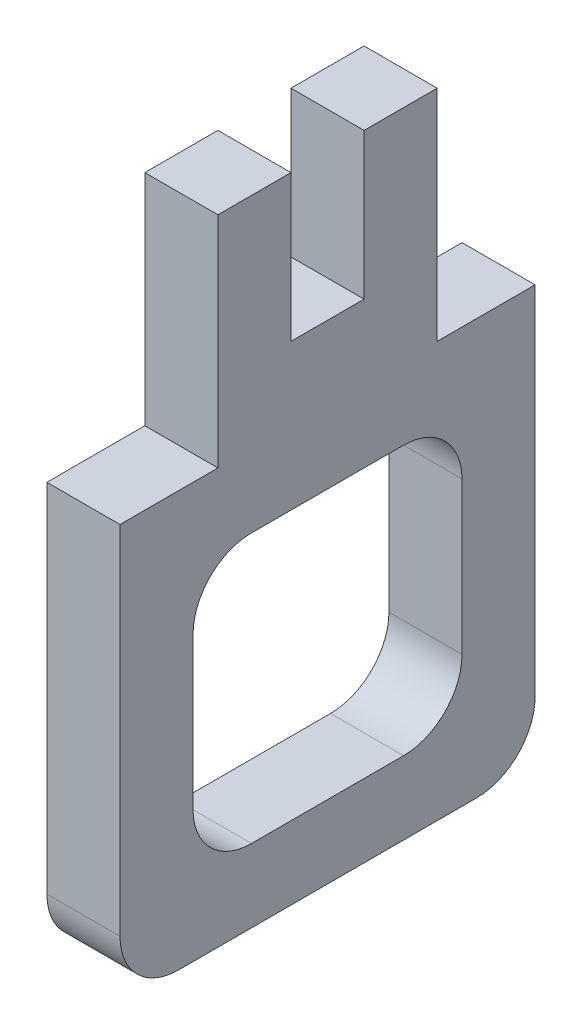
SolidWorks part; units mm, degrees
material "Pine"
ref_plane "Front Plane" through (0, 0, 0) normal (0, 0, 1) x (1, 0, 0)
ref_plane "Top Plane" through (0, 0, 0) normal (0, 1, 0) x (1, 0, 0)
ref_plane "Right Plane" through (0, 0, 0) normal (1, 0, 0) x (0, 0, -1)
sketch "Sketch2" plane through (0, 0, 0) normal (1, 0, 0) x (0, 0, -1)
  line L2 (14.859, 55.118) -> (14.859, 42.418)
  line L3 (14.859, 42.418) -> (21.209, 42.418)
  line L4 (21.209, 42.418) -> (21.209, 55.118)
  line L5 (21.209, 55.118) -> (27.559, 55.118)
  line L7 (30.988, 0) -> (5.08, 0)
  line L9 (11.43, 6.35) -> (24.638, 6.35)
  line L10 (6.35, 11.43) -> (6.35, 24.638)
  line L11 (11.43, 29.718) -> (24.638, 29.718)
  line L12 (29.718, 11.43) -> (29.718, 24.638)
  line L16 (27.559, 55.118) -> (27.559, 36.068)
  line L17 (27.559, 36.068) -> (36.068, 36.068)
  line L18 (36.068, 36.068) -> (36.068, 5.08)
  line L20 (8.509, 36.068) -> (0, 36.068)
  line L21 (0, 36.068) -> (0, 5.08)
  line L22 (14.859, 55.118) -> (8.509, 55.118)
  line L23 (8.509, 55.118) -> (8.509, 36.068)
  arc A0 (11.43, 6.35) -> (6.35, 11.43) centre (11.43, 11.43) cw
  arc A1 (24.638, 6.35) -> (29.718, 11.43) centre (24.638, 11.43) ccw
  arc A2 (24.638, 29.718) -> (29.718, 24.638) centre (24.638, 24.638) cw
  arc A3 (6.35, 24.638) -> (11.43, 29.718) centre (11.43, 24.638) cw
  arc A4 (0, 5.08) -> (5.08, 0) centre (5.08, 5.08) ccw
  arc A5 (36.068, 5.08) -> (30.988, 0) centre (30.988, 5.08) cw
  point P13 (18.034, 42.418)
  point P16 (18.034, 0)
  point P20 (6.35, 6.35)
  point P25 (29.718, 29.718)
  point P29 (6.35, 29.718)
  point P32 (0, 0)
  dimension "D12" = 5.08
  dimension "D13" = 5.08
  dimension "D1" = 6.35
  dimension "D2" = 23.368
  dimension "D3" = 23.368
  dimension "D4" = 6.35
  dimension "D7" = 12.7
  dimension "D5" = 6.35
  dimension "D6" = 6.35
  dimension "D8" = 6.35
  dimension "D9" = 6.35
  dimension "D10" = 6.35
  dimension "D11" = 25.4
extrude "Boss-Extrude1" add sketch "Sketch2" along normal blind 6.35
equation "\"D2@Sketch2\"=\"D3@Sketch2\""
